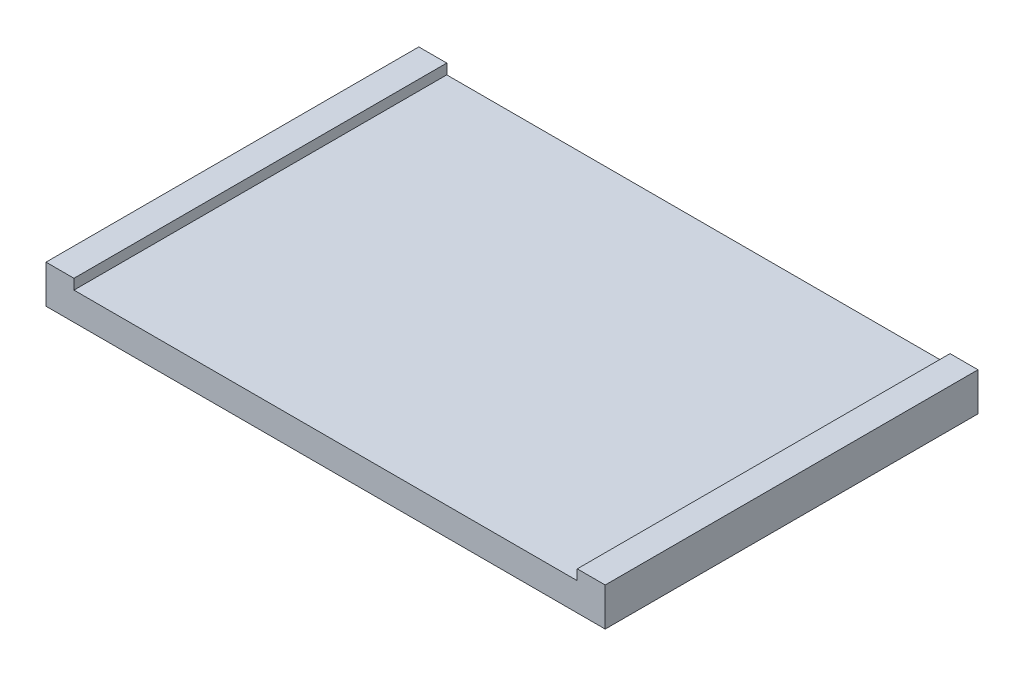
SolidWorks part; units mm, degrees
ref_plane "Front Plane" through (0, 0, 0) normal (0, 0, 1) x (1, 0, 0)
ref_plane "Top Plane" through (0, 0, 0) normal (0, 1, 0) x (1, 0, 0)
ref_plane "Right Plane" through (0, 0, 0) normal (1, 0, 0) x (0, 0, -1)
sketch "Sketch1" plane through (0, 0, 0) normal (0, 1, 0) x (1, 0, 0)
  line L1 (0, 0) -> (30, 0)
  line L2 (0, 0) -> (0, 20)
  line L3 (0, 20) -> (30, 20)
  line L4 (30, 0) -> (30, 20)
  dimension "D1" = 20
  dimension "D2" = 30
extrude "Boss-Extrude1" add sketch "Sketch1" along normal blind 1.5
sketch "Sketch2" plane through (0, 1.5, 0) normal (0, 1, 0) x (1, 0, 0)
  line L0 (0, 20) -> (1.5, 20)
  line L1 (30, 20) -> (0, 20) construction
  line L2 (1.5, 20) -> (1.5, 0)
  line L3 (0, 0) -> (30, 0) construction
  line L4 (1.5, 0) -> (0, 0)
  line L5 (0, 0) -> (0, 20)
  line L6 (28.5, 20) -> (30, 20)
  line L7 (30, 20) -> (30, 0)
  line L8 (30, 0) -> (28.5, 0)
  line L9 (28.5, 0) -> (28.5, 20)
  dimension "D1" = 1.5
  dimension "D2" = 1.5
extrude "Boss-Extrude2" add sketch "Sketch2" along normal blind 0.55
